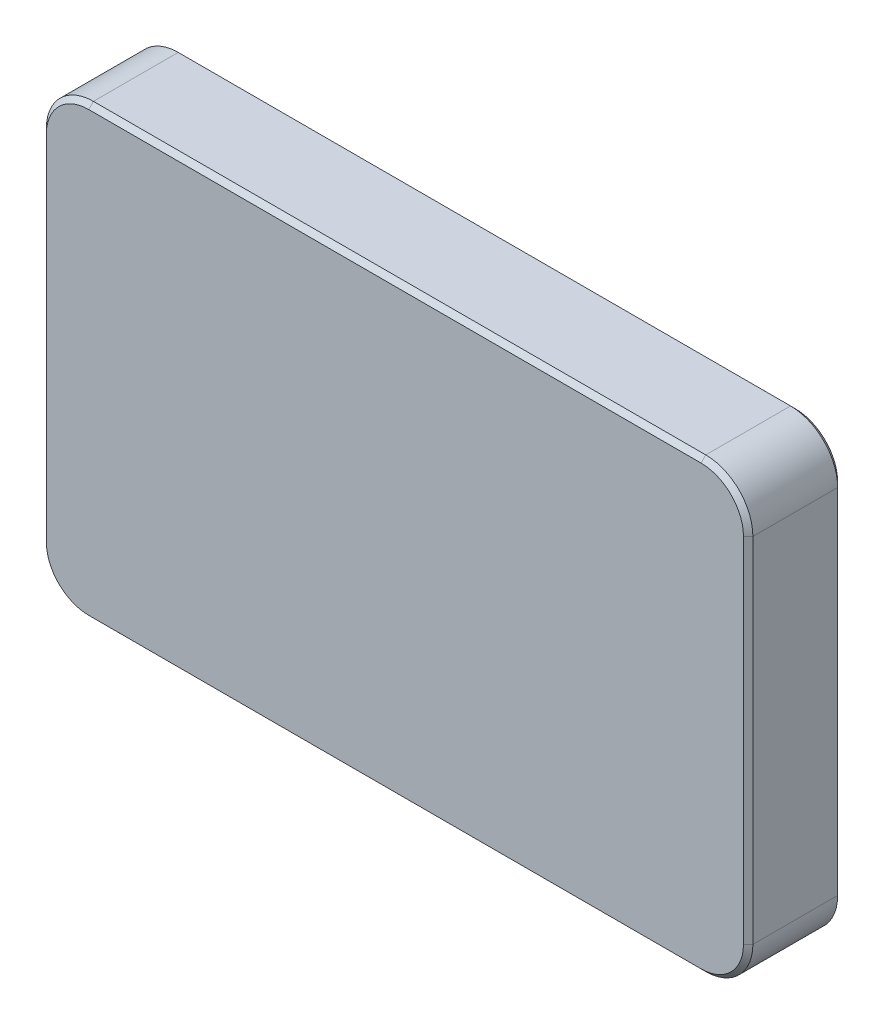
SolidWorks part; units mm, degrees
material "POM Acetal Copolymer"
ref_plane "Front" through (0, 0, 0) normal (0, 0, 1) x (1, 0, 0)
ref_plane "Top" through (0, 0, 0) normal (0, 1, 0) x (1, 0, 0)
ref_plane "Right" through (0, 0, 0) normal (1, 0, 0) x (0, 0, -1)
sketch "Sketch1" plane through (0, 0, 0) normal (0, 0, 1) x (1, 0, 0)
  line L0 (-7.5, 4.75) -> (7.5, 4.75)
  line L1 (-7.5, 4.75) -> (-7.5, -4.75)
  line L2 (-7.5, -4.75) -> (7.5, -4.75)
  line L3 (7.5, 4.75) -> (7.5, -4.75)
  line L4 (0, 4.75) -> (0, -4.75) construction
  dimension "D1" = 9.5
  dimension "D2" = 15
extrude "Boss-Extrude1" add sketch "Sketch1" along normal blind 2
fillet "Fillet1" radius 1 4 edges at (-7.5, -4.75, 1) (-7.5, 4.75, 1) (7.5, -4.75, 1) (7.5, 4.75, 1)
chamfer "Chamfer1" distance 0.1 angle 45 16 edges at (7.2071, -4.4571, 0) (7.5, 0, 0) (7.2071, 4.4571, 0) (0, 4.75, 0) (-7.2071, 4.4571, 0) (-7.5, 0, 0) (-7.2071, -4.4571, 0) (0, -4.75, 0) (-7.2071, 4.4571, 2) (0, 4.75, 2) (7.2071, 4.4571, 2) (7.5, 0, 2) (7.2071, -4.4571, 2) (0, -4.75, 2) (-7.2071, -4.4571, 2) (-7.5, 0, 2)
